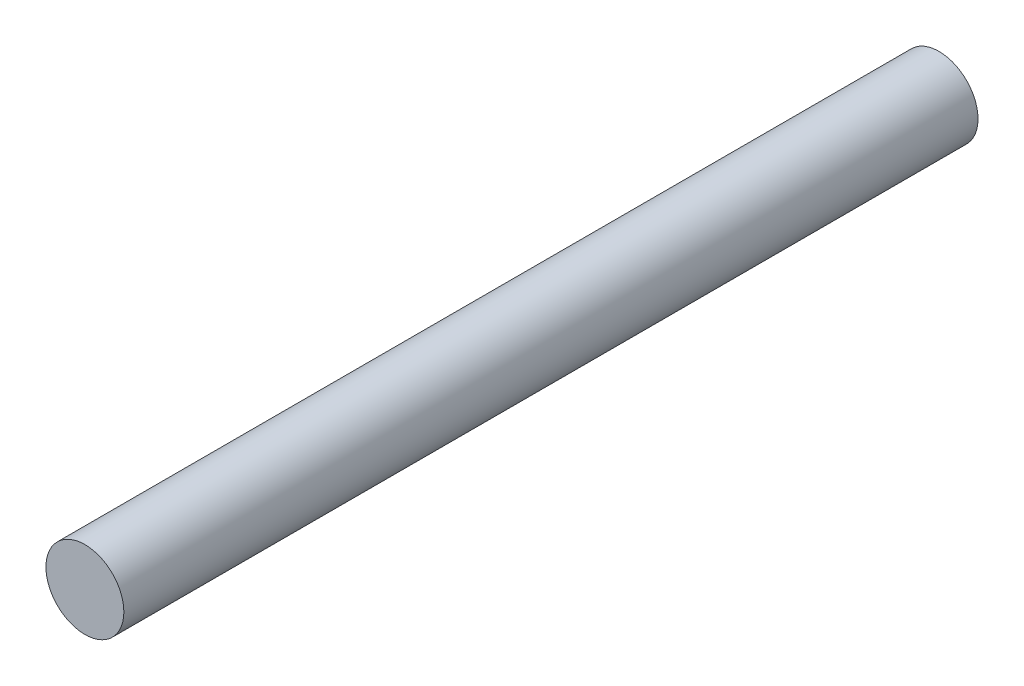
SolidWorks part; units mm, degrees
ref_plane "Front" through (0, 0, 0) normal (0, 0, 1) x (1, 0, 0)
ref_plane "Top" through (0, 0, 0) normal (0, 1, 0) x (1, 0, 0)
ref_plane "Right" through (0, 0, 0) normal (1, 0, 0) x (0, 0, -1)
sketch "Sketch1" plane through (0, 0, 0) normal (0, 0, 1) x (1, 0, 0)
  circle A0 centre (0, 0) radius 6.35
  dimension "D1" = 12.7
extrude "Boss-Extrude1" add sketch "Sketch1" against normal blind 139.192
